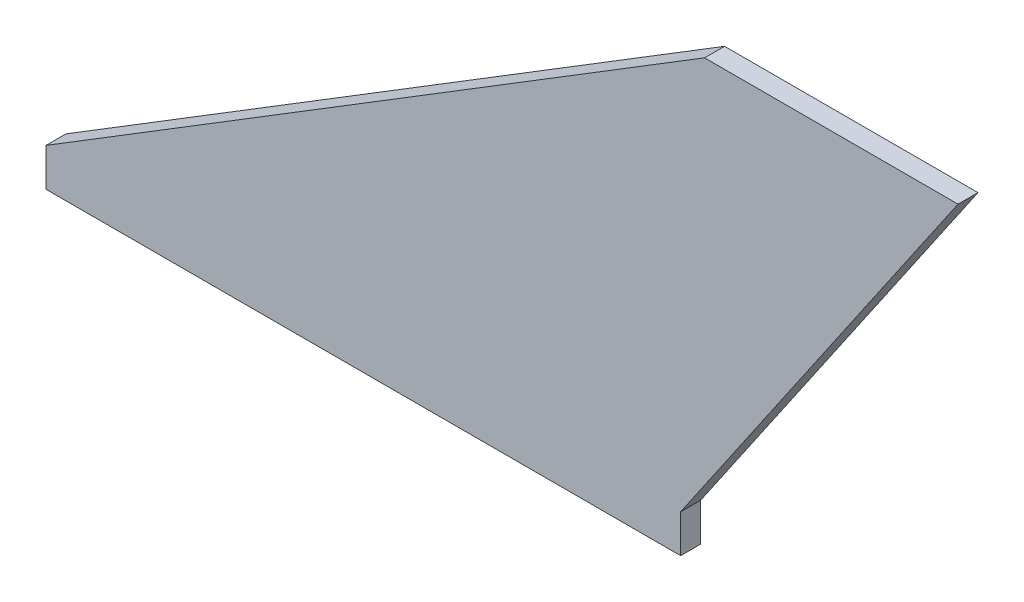
SolidWorks part; units mm, degrees
material "C-Glass Fiber"
ref_plane "Front Plane" through (0, 0, 0) normal (0, 0, 1) x (1, 0, 0)
ref_plane "Top Plane" through (0, 0, 0) normal (0, 1, 0) x (1, 0, 0)
ref_plane "Right Plane" through (0, 0, 0) normal (1, 0, 0) x (0, 0, -1)
sketch "Sketch1" plane through (0, 0, 0) normal (0, 0, 1) x (1, 0, 0)
  line L0 (0, 0) -> (318, 0)
  line L1 (318, 0) -> (318, 19.05)
  line L2 (318, 19.05) -> (457, 222.05)
  line L3 (457, 222.05) -> (330, 222.05)
  line L4 (330, 222.05) -> (0, 19.05)
  line L5 (0, 19.05) -> (0, 0)
  line L6 (0, 19.05) -> (318, 19.05) construction
  dimension "D1" = 318
  dimension "D2" = 19.05
  dimension "D3" = 203
  dimension "D4" = 330
  dimension "D5" = 127
extrude "Boss-Extrude1" add sketch "Sketch1" along normal blind 10
